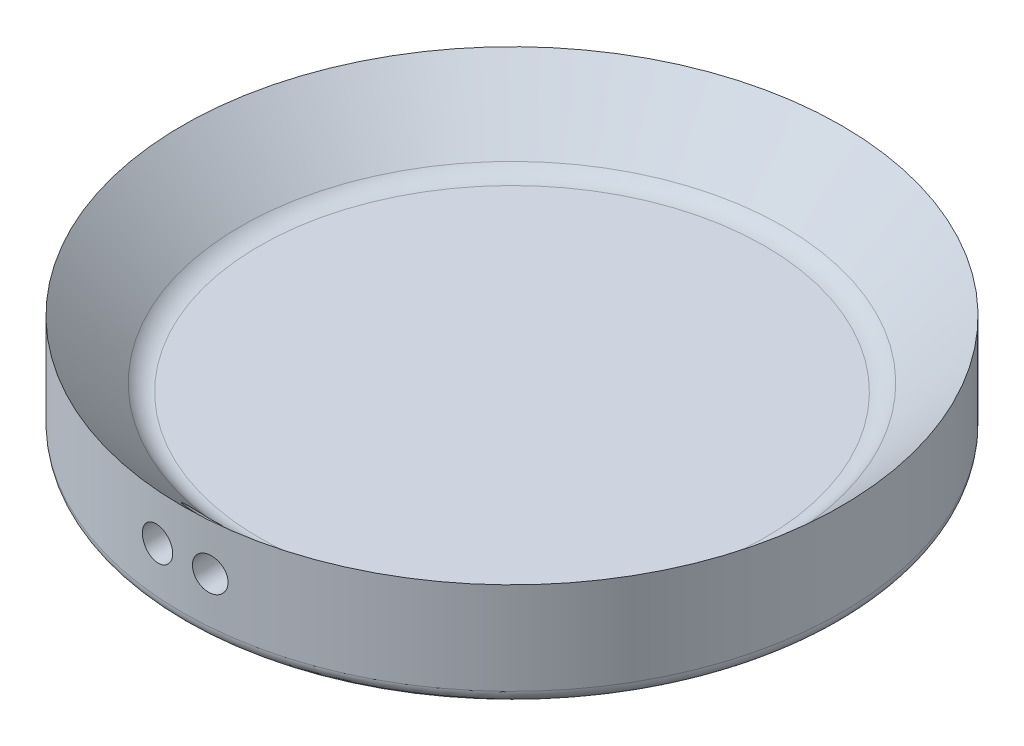
SolidWorks part; units mm, degrees
ref_plane "Front Plane" through (0, 0, 0) normal (0, 0, 1) x (1, 0, 0)
ref_plane "Top Plane" through (0, 0, 0) normal (0, 1, 0) x (1, 0, 0)
ref_plane "Right Plane" through (0, 0, 0) normal (1, 0, 0) x (0, 0, -1)
sketch "Sketch3" plane through (0, 0, 0) normal (0, 0, 1) x (1, 0, 0)
  line L4 (-23, 0) -> (0, 0)
  line L9 (-19.1716, 3) -> (0, 3)
  line L10 (0, 0) -> (0, 3)
  line L12 (-20, 3) -> (-20, 8) construction
  line L13 (-20, 8) -> (-25, 8) construction
  line L15 (-25, 8) -> (-20.5858, 3.5858)
  line L16 (-23, 0) -> (-24, 0)
  line L17 (-25, 1) -> (-25, 8)
  arc A4 (-25, 1) -> (-24, 0) centre (-24, 1) ccw
  arc A5 (-20.5858, 3.5858) -> (-19.1716, 3) centre (-19.1716, 5) ccw
  dimension "D1" = 5
  dimension "D6" = 1
  dimension "D7" = 2
  dimension "D2" = 23
  dimension "D3" = 20
  dimension "D4" = 3
  dimension "D5" = 5
revolve "Revolve3" add sketch "Sketch3" angle 360 about L10
ref_plane "Plane1" through (0, 0, 25) normal (0, 0, 1) x (1, 0, 0)
sketch "Sketch5" plane through (0, 0, 25) normal (0, 0, 1) x (1, 0, 0)
  line L0 (0, 8) -> (0, 1) construction
  line L2 (25, 8) -> (-25, 8) construction
  line L3 (-2, 4.5) -> (2, 4.5) construction
  circle A0 centre (-2, 4.5) radius 1.25
  circle A1 centre (2, 4.5) radius 1.25
  point P8 (0, 4.5)
  point P9 (0, 4.5)
  dimension "D3" = 2.5
  dimension "D4" = 2.5
  dimension "D1" = 7
  dimension "D2" = 4
extrude "Cut-Extrude1" cut sketch "Sketch5" against normal up to next
